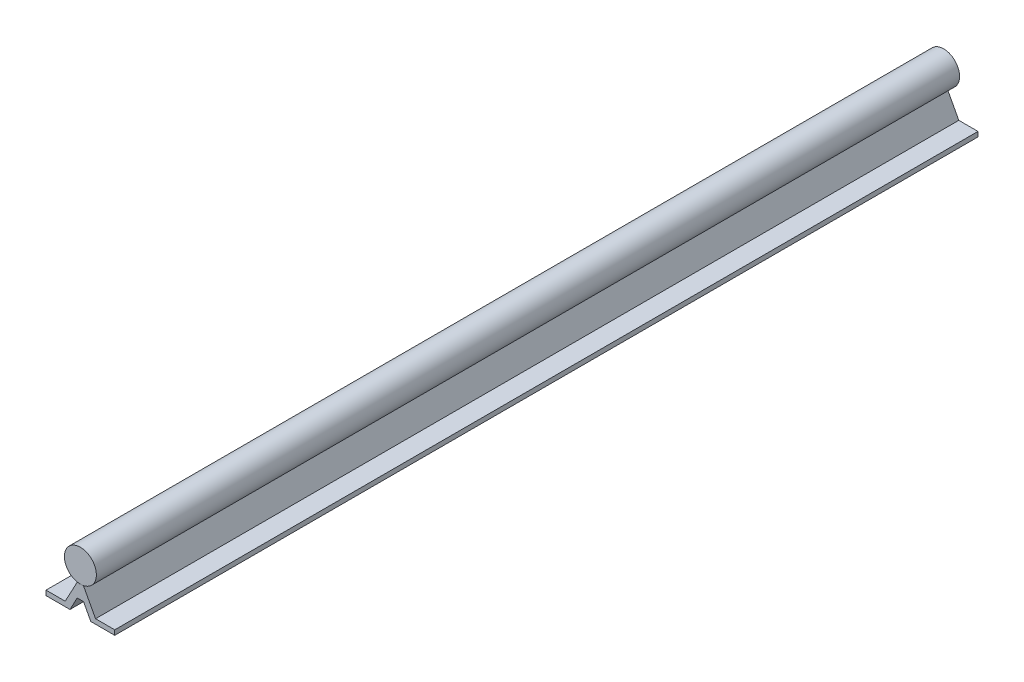
SolidWorks part; units mm, degrees
ref_plane "Alzado" through (0, 0, 0) normal (0, 0, 1) x (1, 0, 0)
ref_plane "Planta" through (0, 0, 0) normal (0, 1, 0) x (1, 0, 0)
ref_plane "Vista lateral" through (0, 0, 0) normal (1, 0, 0) x (0, 0, -1)
sketch "Croquis1" plane through (0, 0, 0) normal (0, 0, 1) x (1, 0, 0)
  line L0 (6.5, 0) -> (21.5, 0)
  line L1 (6.5, 0) -> (-6.5, 0)
  line L2 (-6.5, 0) -> (-21.5, 0)
  line L3 (-21.5, 0) -> (-21.5, 3)
  line L4 (-21.5, 3) -> (-9.5, 3)
  line L5 (0, 0) -> (0, 17)
  line L6 (-9.5, 3) -> (-2, 17)
  line L7 (2, 17) -> (-2, 17)
  line L8 (-6.5, 0) -> (-2, 8.5)
  line L9 (-2, 8.5) -> (2, 8.5)
  line L10 (0, 17) -> (0, 27)
  line L12 (0, -55) -> (0, 55) construction
  line L13 (6.5, 0) -> (2, 8.5)
  line L14 (9.5, 3) -> (2, 17)
  line L15 (21.5, 3) -> (9.5, 3)
  line L16 (6.5, 0) -> (21.5, 0)
  line L17 (21.5, 3) -> (21.5, 0)
  circle A0 centre (0, 27) radius 10
  point P18 (0, 8.5)
  point P21 (0, 0)
  point P22 (21.7397, 0)
  dimension "D1" = 13
  dimension "12" = 12
extrude "Saliente-Extruir1" add sketch "Croquis1" along normal blind 540
